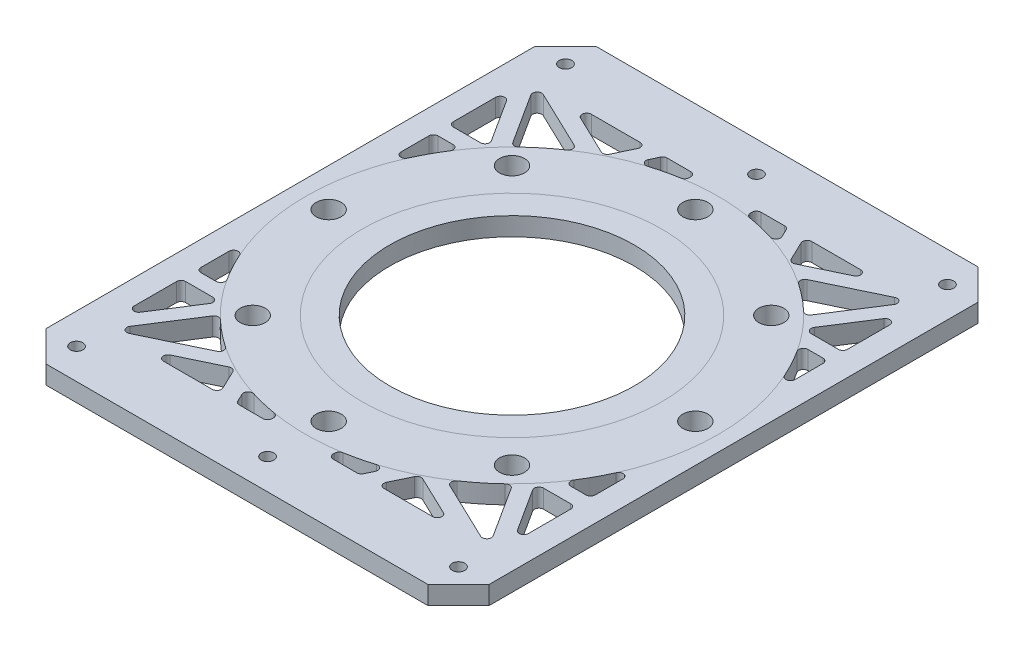
SolidWorks part; units mm, degrees
material "A-玻璃纤维"
ref_plane "前视基准面" through (0, 0, 0) normal (0, 0, 1) x (1, 0, 0)
ref_plane "上视基准面" through (0, 0, 0) normal (0, 1, 0) x (1, 0, 0)
ref_plane "右视基准面" through (0, 0, 0) normal (1, 0, 0) x (0, 0, -1)
sketch "草图1" plane through (0, 0, 0) normal (0, 1, 0) x (1, 0, 0)
  line L0 (-62.5, 80) -> (-62.5, -80) construction
  line L1 (-72.5, 90) -> (72.5, 90)
  line L2 (-72.5, 90) -> (-72.5, -90)
  line L3 (-72.5, -90) -> (72.5, -90)
  line L4 (72.5, 90) -> (72.5, -90)
  line L5 (0, -90) -> (0, 90) construction
  line L6 (-72.5, 0) -> (72.5, 0) construction
  line L7 (-62.5, -80) -> (62.5, -80) construction
  line L8 (62.5, 80) -> (62.5, -80) construction
  line L9 (-62.5, 80) -> (62.5, 80) construction
  circle A0 centre (-62.5, 80) radius 2.05
  circle A1 centre (0, 80) radius 2.05
  circle A2 centre (62.5, 80) radius 2.05
  circle A4 centre (-62.5, 0) radius 2.05 construction
  circle A5 centre (62.5, 0) radius 2.05 construction
  circle A6 centre (62.5, -80) radius 2.05
  circle A7 centre (0, -80) radius 2.05
  circle A8 centre (-62.5, -80) radius 2.05
  point P40 (0, 0)
  dimension "D3" = 4.1
  dimension "D4" = 145
  dimension "D1" = 180
  dimension "D2" = 10
extrude "凸台-拉伸1" add sketch "草图1" along normal blind 6
sketch "草图2" plane through (0, 6, 0) normal (0, 1, 0) x (1, 0, 0)
  circle A0 centre (0, 0) radius 60 construction
  circle A2 centre (0, 60) radius 4.1
  circle A3 centre (42.4264, 42.4264) radius 4.1
  circle A4 centre (60, 0) radius 4.1
  circle A5 centre (42.4264, -42.4264) radius 4.1
  circle A6 centre (0, -60) radius 4.1
  circle A7 centre (-42.4264, -42.4264) radius 4.1
  circle A8 centre (-60, 0) radius 4.1
  circle A9 centre (-42.4264, 42.4264) radius 4.1
  point P21 (0, 0)
  dimension "D1" = 120
  dimension "D2" = 8.2
  dimension "D3" = 8
extrude "切除-拉伸1" cut sketch "草图2" against normal blind 6
sketch "草图3" plane through (0, 6, 0) normal (0, 1, 0) x (1, 0, 0)
  line L0 (72.5, -90) -> (72.5, 90) construction
  line L1 (-72.5, 90) -> (72.5, 90) construction
  line L2 (-72.5, 90) -> (-72.5, 70) construction
  line L3 (-72.5, 70) -> (72.5, 70) construction
  line L4 (72.5, 90) -> (72.5, 70) construction
  line L5 (0, 70) -> (0, 90) construction
  line L6 (-72.5, 80) -> (72.5, 80) construction
  line L7 (0, 0) -> (105.1908, 0) construction
  line L8 (-72.5, -80) -> (72.5, -80) construction
  line L9 (0, -70) -> (0, -90) construction
  line L10 (72.5, -90) -> (72.5, -70) construction
  line L11 (-72.5, -70) -> (72.5, -70) construction
  line L12 (-72.5, -90) -> (-72.5, -70) construction
  line L13 (-72.5, -90) -> (72.5, -90) construction
  line L14 (-10, 70) -> (-64.5, 70)
  line L15 (-64.5, 70) -> (-64.5, 19.8997)
  line L16 (-72.5, 90) -> (-72.5, -90) construction
  line L17 (-10, 70) -> (-10, 66.7551)
  line L18 (10, 70) -> (10, 66.7551)
  line L19 (64.5, 70) -> (64.5, 19.8997)
  line L20 (10, 70) -> (64.5, 70)
  line L21 (64.5, -70) -> (64.5, -19.8997)
  line L22 (10, -70) -> (64.5, -70)
  line L23 (10, -70) -> (10, -66.7551)
  line L24 (-10, -70) -> (-10, -66.7551)
  line L25 (-64.5, -70) -> (-64.5, -19.8997)
  line L26 (-10, -70) -> (-64.5, -70)
  line L27 (-64.5, 38.783) -> (-55.2461, 38.783)
  line L28 (-64.5, 43.783) -> (-51.3741, 43.783)
  line L29 (-51.3741, 43.783) -> (-64.5, 64.2574)
  line L30 (-62.2422, 70) -> (-47.873, 47.586)
  line L31 (-35.7007, 57.2862) -> (-62.2422, 70)
  line L32 (-50.6684, 70) -> (-30.3752, 60.2793)
  line L33 (-30.3752, 60.2793) -> (-25.7189, 70)
  line L34 (-23.3726, 63.3243) -> (-20.1748, 70)
  line L35 (23.3726, 63.3243) -> (20.1748, 70)
  line L36 (30.3752, 60.2793) -> (25.7189, 70)
  line L37 (50.6684, 70) -> (30.3752, 60.2793)
  line L38 (35.7007, 57.2862) -> (62.2422, 70)
  line L39 (64.5, 38.783) -> (55.2461, 38.783)
  line L40 (64.5, 43.783) -> (51.3741, 43.783)
  line L41 (62.2422, 70) -> (47.873, 47.586)
  line L42 (51.3741, 43.783) -> (64.5, 64.2574)
  line L43 (64.5, -38.783) -> (55.2461, -38.783)
  line L44 (64.5, -43.783) -> (51.3741, -43.783)
  line L45 (51.3741, -43.783) -> (64.5, -64.2574)
  line L46 (62.2422, -70) -> (47.873, -47.586)
  line L47 (35.7007, -57.2862) -> (62.2422, -70)
  line L48 (50.6684, -70) -> (30.3752, -60.2793)
  line L49 (30.3752, -60.2793) -> (25.7189, -70)
  line L50 (23.3726, -63.3243) -> (20.1748, -70)
  line L51 (-23.3726, -63.3243) -> (-20.1748, -70)
  line L52 (-30.3752, -60.2793) -> (-25.7189, -70)
  line L53 (-50.6684, -70) -> (-30.3752, -60.2793)
  line L54 (-35.7007, -57.2862) -> (-62.2422, -70)
  line L55 (-62.2422, -70) -> (-47.873, -47.586)
  line L56 (-51.3741, -43.783) -> (-64.5, -64.2574)
  line L57 (-64.5, -43.783) -> (-51.3741, -43.783)
  line L58 (-64.5, -38.783) -> (-55.2461, -38.783)
  circle A0 centre (0, 0) radius 40
  circle A1 centre (0, 0) radius 67.5
  circle A2 centre (0, -80) radius 2.05 construction
  point P20 (0, -80)
  point P119 (0, 80)
  dimension "D1" = 80
  dimension "D3" = 135
  dimension "D2" = 20
  dimension "D4" = 8
  dimension "D5" = 20
  dimension "D6" = 5
  dimension "D7" = 5
  dimension "D8" = 5
  dimension "D9" = 5
  dimension "D10" = 20.1748
  dimension "D11" = 23.3726
  dimension "D12" = 47.873
extrude "切除-拉伸2" cut sketch "草图3" against normal blind 10 contours A1 L27 L15 | L28 L29 L15 | A1 L31 L30 | L32 L33 L14 | A1 L17 L14 L34 | A1 L35 L20 L18 | L37 L20 L36 | A1 L41 L38 | L42 L40 L19 | A1 L19 L39 | A1 L43 L21 | L44 L45 L21 | A1 L47 L46 | L48 L49 L22 | A1 L23 L22 L50 | A1 L51 L26 L24 | L53 L26 L52 | A1 L55 L54 | L57 L25 L56 | A1 L25 L58 | A0
fillet "圆角1" radius 1.5 64 edges at (-64.5, 3, -19.8997) (-10, 3, -66.7551) (-10, 3, -70) (-10, 3, 66.7551) (-10, 3, 70) (-64.5, 3, 19.8997) (10, 3, -66.7551) (64.5, 3, -19.8997) (64.5, 3, 19.8997) (10, 3, 70) (10, 3, 66.7551) (10, 3, -70) (-23.3726, 3, -63.3243) (-20.1748, 3, -70) (-25.7189, 3, -70) (-30.3752, 3, -60.2793) (-50.6684, 3, -70) (-64.5, 3, -64.2574) (-51.3741, 3, -43.783) (35.7007, 3, -57.2862) (62.2422, 3, -70) (47.873, 3, -47.586) (30.3752, 3, -60.2793) (25.7189, 3, -70) (50.6684, 3, -70) (-30.3752, 3, 60.2793) (-25.7189, 3, 70) (-50.6684, 3, 70) (23.3726, 3, 63.3243) (20.1748, 3, 70) (25.7189, 3, 70) (30.3752, 3, 60.2793) (50.6684, 3, 70) (64.5, 3, 64.2574) (51.3741, 3, 43.783) (64.5, 3, 43.783) (64.5, 3, 38.783) (55.2461, 3, 38.783) (-51.3741, 3, 43.783) (-64.5, 3, 64.2574) (-64.5, 3, 43.783) (-55.2461, 3, 38.783) (-64.5, 3, 38.783) (-64.5, 3, -38.783) (-55.2461, 3, -38.783) (-35.7007, 3, 57.2862) (-62.2422, 3, 70) (-47.873, 3, 47.586) (55.2461, 3, -38.783) (64.5, 3, -38.783) (47.873, 3, 47.586) (62.2422, 3, 70) (35.7007, 3, 57.2862) (-20.1748, 3, 70) (-23.3726, 3, 63.3243) (20.1748, 3, -70) (23.3726, 3, -63.3243) (64.5, 3, -64.2574) (64.5, 3, -43.783) (51.3741, 3, -43.783) (-47.873, 3, -47.586) (-62.2422, 3, -70) (-35.7007, 3, -57.2862) (-64.5, 3, -43.783)
sketch "草图4" plane through (0, 6, 0) normal (0, 1, 0) x (1, 0, 0)
  circle A0 centre (0, 0) radius 49
  circle A1 centre (0, 0) radius 67.5
  dimension "D1" = 98
  dimension "D2" = 135
split line "分割线1"
chamfer "倒角1" distance 10 angle 45 4 edges at (-72.5, 3, 90) (72.5, 3, 90) (72.5, 3, -90) (-72.5, 3, -90)
